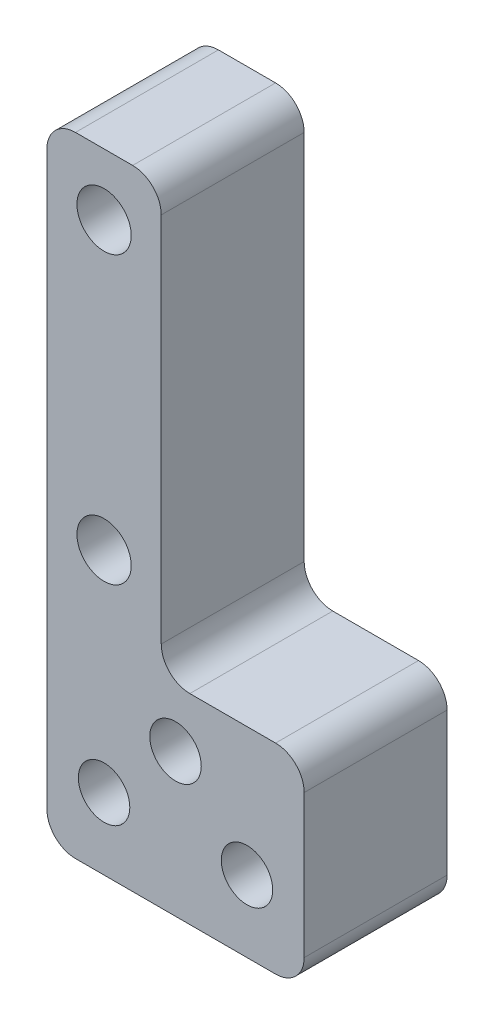
SolidWorks part; units mm, degrees
ref_plane "Front Plane" through (0, 0, 0) normal (0, 0, 1) x (1, 0, 0)
ref_plane "Top Plane" through (0, 0, 0) normal (0, 1, 0) x (1, 0, 0)
ref_plane "Right Plane" through (0, 0, 0) normal (1, 0, 0) x (0, 0, -1)
sketch "Sketch1" plane through (0, 0, 0) normal (0, 0, 1) x (1, 0, 0)
  line L0 (0, -44.069) -> (12.7, -44.069) construction
  line L1 (-5.08, -32.639) -> (5.08, -32.639)
  line L2 (-5.08, -32.639) -> (-5.08, 5.461)
  line L3 (-5.08, 5.461) -> (5.08, 5.461)
  line L4 (5.08, -32.639) -> (5.08, 5.461)
  line L5 (6.35, -44.069) -> (6.35, -37.719) construction
  line L7 (-5.08, -32.639) -> (17.78, -32.639)
  line L8 (-5.08, -32.639) -> (-5.08, -50.419)
  line L9 (-5.08, -50.419) -> (17.78, -50.419)
  line L10 (17.78, -32.639) -> (17.78, -50.419)
  circle A0 centre (0, 0) radius 2.413
  circle A1 centre (0, -25.4) radius 2.413
  circle A2 centre (0, -44.069) radius 2.286
  circle A3 centre (12.7, -44.069) radius 2.286
  circle A4 centre (6.35, -37.719) radius 2.286
  dimension "D1" = 17.78
  dimension "D2" = 4.572
  dimension "D3" = 4.826
  dimension "D12" = 6.35
  dimension "D4" = 5.08
  dimension "D5" = 6.35
  dimension "D6" = 10.16
  dimension "D7" = 25.4
  dimension "D8" = 5.461
  dimension "D9" = 38.1
  dimension "D10" = 5.08
  dimension "D11" = 12.7
extrude "Boss-Extrude1" add sketch "Sketch1" along normal blind 12.7 contours L10 L7 L1 L8 L9 A3 A2 | L1 L4 L3 L2 A1 A0
fillet "Fillet1" radius 2.54 6 edges at (17.78, -50.419, 6.35) (17.78, -32.639, 6.35) (-5.08, -50.419, 6.35) (-5.08, 5.461, 6.35) (5.08, 5.461, 6.35) (5.08, -32.639, 6.35)
